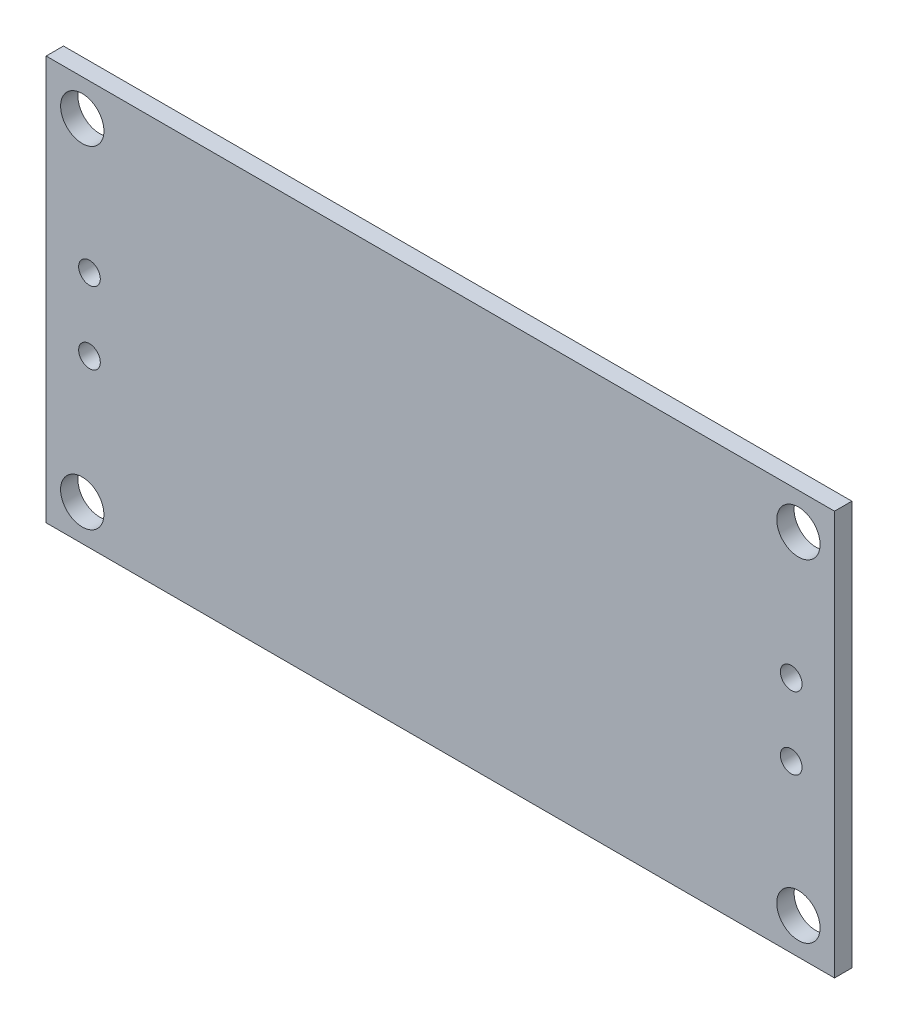
SolidWorks part; units mm, degrees
ref_plane "Plano frontal" through (0, 0, 0) normal (0, 0, 1) x (1, 0, 0)
ref_plane "Plano superior" through (0, 0, 0) normal (0, 1, 0) x (1, 0, 0)
ref_plane "Plano direito" through (0, 0, 0) normal (1, 0, 0) x (0, 0, -1)
sketch "Esboço1" plane through (0, 0, 0) normal (0, 0, 1) x (1, 0, 0)
  line L1 (-27.3, -14) -> (27.3, -14)
  line L2 (-27.3, -14) -> (-27.3, 14)
  line L3 (-27.3, 14) -> (27.3, 14)
  line L4 (27.3, -14) -> (27.3, 14)
  line L5 (-27.3, -14) -> (27.3, 14) construction
  line L6 (-27.3, 14) -> (27.3, -14) construction
  point P0 (0, 0)
  dimension "D1" = 54.6
  dimension "D2" = 28
extrude "Ressalto-extrusão1" add sketch "Esboço1" along normal blind 1.2
sketch "Esboço2" plane through (0, 0, 1.2) normal (0, 0, 1) x (1, 0, 0)
  line L0 (0, 14) -> (0, -14) construction
  line L1 (27.3, 14) -> (-27.3, 14) construction
  line L2 (-27.3, -14) -> (27.3, -14) construction
  line L3 (-27.3, 0) -> (27.3, 0) construction
  line L4 (-27.3, 14) -> (-27.3, -14) construction
  line L5 (27.3, -14) -> (27.3, 14) construction
  line L6 (-24.8, 11.5) -> (-27.3, 11.5) construction
  line L7 (-24.8, 11.5) -> (-24.8, 14) construction
  circle A0 centre (-24.8, 11.5) radius 1.5
  circle A1 centre (24.8, 11.5) radius 1.5
  circle A2 centre (-24.8, -11.5) radius 1.5
  circle A3 centre (24.8, -11.5) radius 1.5
  dimension "D1" = 3
  dimension "D2" = 2.5
extrude "Corte-extrusão1" cut sketch "Esboço2" against normal through all
sketch "Esboço3" plane through (0, 0, 1.2) normal (0, 0, 1) x (1, 0, 0)
  line L0 (0, 14) -> (0, -14) construction
  line L1 (27.3, 14) -> (-27.3, 14) construction
  line L2 (-27.3, -14) -> (27.3, -14) construction
  line L3 (-27.3, 0) -> (27.3, 0) construction
  line L4 (-27.3, 14) -> (-27.3, -14) construction
  line L5 (27.3, -14) -> (27.3, 14) construction
  circle A0 centre (24.3, 2.5) radius 2 construction
  circle A1 centre (24.3, 2.5) radius 0.75
  circle A2 centre (24.3, -2.5) radius 0.75
  circle A3 centre (-24.3, -2.5) radius 0.75
  circle A4 centre (-24.3, 2.5) radius 0.75
  dimension "D1" = 4
  dimension "D4" = 1.5
  dimension "D2" = 3
  dimension "D3" = 2.5
extrude "Corte-extrusão2" cut sketch "Esboço3" against normal through all
sketch "Picture" plane through (0, 0, 1.2) normal (0, 0, 1) x (1, 0, 0)
  line L0 (67.4439, 131.9843) -> (446.1106, 131.9843) construction
